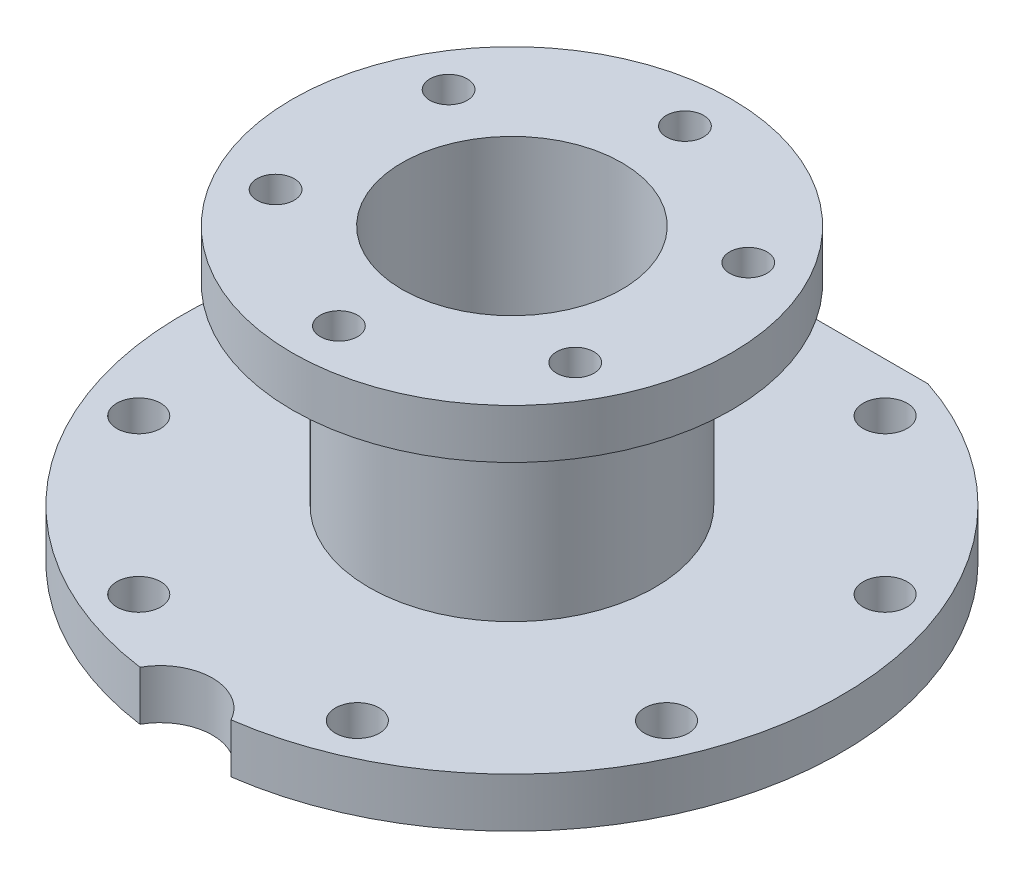
SolidWorks part; units mm, degrees
ref_plane "前视基准面" through (0, 0, 0) normal (0, 0, 1) x (1, 0, 0)
ref_plane "上视基准面" through (0, 0, 0) normal (0, 1, 0) x (1, 0, 0)
ref_plane "右视基准面" through (0, 0, 0) normal (1, 0, 0) x (0, 0, -1)
sketch "草图1" plane through (0, 0, 0) normal (0, 1, 0) x (1, 0, 0)
  line L0 (-18.735, 57) -> (18.735, 57)
  line L1 (0, 0) -> (-48.0417, 19.8995) construction
  line L2 (0, 0) -> (-92.9336, 0) construction
  circle A0 centre (0, 0) radius 52 construction
  arc A2 (8.294, -59.424) -> (18.735, 57) centre (0, 0) ccw
  arc A3 (8.294, -59.424) -> (-8.294, -59.424) centre (0, -64) ccw
  arc A4 (-18.735, 57) -> (-8.294, -59.424) centre (0, 0) ccw
  circle A5 centre (-48.0417, 19.8995) radius 4
  circle A6 centre (-19.8995, 48.0417) radius 4
  circle A7 centre (19.8995, 48.0417) radius 4
  circle A8 centre (48.0417, 19.8995) radius 4
  circle A9 centre (48.0417, -19.8995) radius 4
  circle A10 centre (19.8995, -48.0417) radius 4
  circle A11 centre (-19.8995, -48.0417) radius 4
  circle A12 centre (-48.0417, -19.8995) radius 4
  dimension "D1" = 120
  dimension "D2" = 104
  dimension "D7" = 8
  dimension "D4" = 57
  dimension "D5" = 64
  dimension "D6" = 22.5
  dimension "D8" = 8
extrude "凸台-拉伸1" add sketch "草图1" along normal blind 9
sketch "草图2" plane through (0, 9, 0) normal (0, 1, 0) x (1, 0, 0)
  circle A0 centre (0, 0) radius 26
  dimension "D1" = 52
extrude "凸台-拉伸2" add sketch "草图2" along normal blind 35
sketch "草图3" plane through (0, 44, 0) normal (0, 1, 0) x (1, 0, 0)
  circle A0 centre (0, 0) radius 40
  dimension "D1" = 80
extrude "凸台-拉伸3" add sketch "草图3" along normal blind 9
hole_wizard "M8 螺纹孔1" positions "草图4" profile "草图5" tap size "M8" standard "GB"
sketch "草图4" plane through (0, 53, 0) normal (0, 1, 0) x (1, 0, 0)
  point P0 (0, 31.5)
  dimension "D1" = 31.5
sketch "草图5" plane through (0, 53, -31.5) normal (1, 0, 0) x (0, 0, 1)
  line L0 (0, 0) -> (0, 9)
  line L1 (0, 9) -> (3.4, 9)
  line L2 (3.4, 9) -> (3.4, 0)
  line L5 (3.4, 0) -> (0, 0)
  line L11 (0, -6.35) -> (0, 107.95) construction
  dimension "通孔螺纹孔钻头直径" = 6.8
  dimension "通孔螺纹孔钻头深度" = 9
cosmetic thread "孔螺蚊线1" parameters "D2"=8
pattern_circular "阵列(圆周)1" count 6 over 360 about axis through (0, 0, 0) along (0, 1, 0) of "M8 螺纹孔1"
cosmetic thread "孔螺蚊线2" parameters "D2"=8
cosmetic thread "孔螺蚊线3" parameters "D2"=8
cosmetic thread "孔螺蚊线4" parameters "D2"=8
cosmetic thread "孔螺蚊线5" parameters "D2"=8
cosmetic thread "孔螺蚊线6" parameters "D2"=8
sketch "草图6" plane through (0, 53, 0) normal (0, 1, 0) x (1, 0, 0)
  circle A0 centre (0, 0) radius 20
  dimension "D1" = 40
extrude "切除-拉伸1" cut sketch "草图6" against normal through all
sketch "草图7" plane through (0, 0, 0) normal (0, -1, 0) x (1, 0, 0)
  circle A0 centre (0, 0) radius 37.5
  dimension "D1" = 75
extrude "切除-拉伸2" cut sketch "草图7" against normal blind 6
sketch "草图8" plane through (0, 53, 0) normal (0, 1, 0) x (1, 0, 0)
  circle A0 centre (0, 31.5) radius 1.5
  dimension "D1" = 3
extrude "切除-拉伸3" cut sketch "草图8" against normal through all
